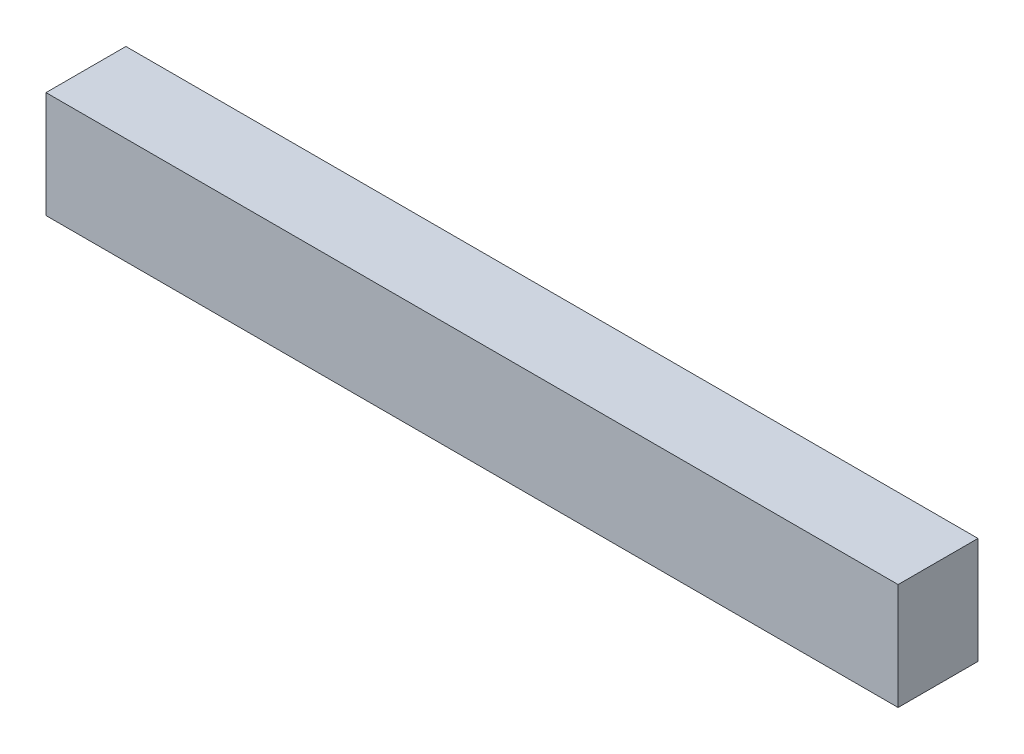
SolidWorks part; units mm, degrees
ref_plane "Front Plane" through (0, 0, 0) normal (0, 0, 1) x (1, 0, 0)
ref_plane "Top Plane" through (0, 0, 0) normal (0, 1, 0) x (1, 0, 0)
ref_plane "Right Plane" through (0, 0, 0) normal (1, 0, 0) x (0, 0, -1)
sketch "Sketch1" plane through (0, 0, 0) normal (0, 1, 0) x (1, 0, 0)
  line L1 (0, 0) -> (32, 0)
  line L2 (0, 0) -> (0, 3)
  line L3 (0, 3) -> (32, 3)
  line L4 (32, 0) -> (32, 3)
  dimension "D1" = 32
  dimension "D2" = 3
extrude "Boss-Extrude1" add sketch "Sketch1" along normal blind 4
